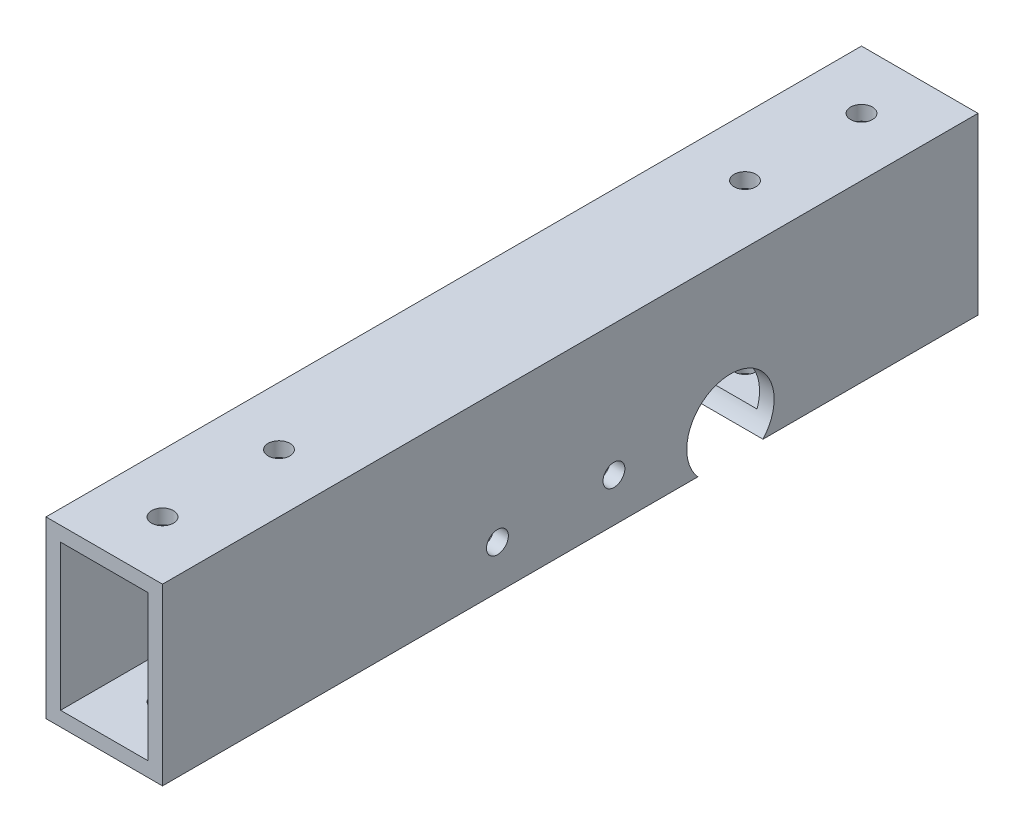
SolidWorks part; units mm, degrees
material "6063-T1"
ref_plane "Front Plane" through (0, 0, 0) normal (0, 0, 1) x (1, 0, 0)
ref_plane "Top Plane" through (0, 0, 0) normal (0, 1, 0) x (1, 0, 0)
ref_plane "Right Plane" through (0, 0, 0) normal (1, 0, 0) x (0, 0, -1)
sketch "Sketch1" plane through (0, 0, 0) normal (0, 0, 1) x (1, 0, 0)
  line L1 (-12.7, 19.05) -> (12.7, 19.05)
  line L2 (-12.7, 19.05) -> (-12.7, -19.05)
  line L3 (-12.7, -19.05) -> (12.7, -19.05)
  line L4 (12.7, 19.05) -> (12.7, -19.05)
  line L5 (-12.7, 19.05) -> (12.7, -19.05) construction
  line L6 (-12.7, -19.05) -> (12.7, 19.05) construction
  point P0 (0, 0)
  dimension "D1" = 25.4
  dimension "D2" = 38.1
extrude "Boss-Extrude1" add sketch "Sketch1" along normal blind 177.8
shell "Shell1" thickness 3.175
sketch "Sketch2" plane through (12.7, 0, 0) normal (1, 0, 0) x (0, 0, -1)
  line L0 (-177.8, -19.05) -> (0, -19.05) construction
  line L1 (0, -19.05) -> (0, 19.05) construction
  circle A0 centre (-53.975, -12.7) radius 9.525
  dimension "D1" = 19.05
  dimension "D2" = 6.35
  dimension "D3" = 53.975
extrude "Cut-Extrude1" cut sketch "Sketch2" against normal through all
sketch "Sketch3" plane through (0, 19.05, 0) normal (0, 1, 0) x (1, 0, 0)
  line L0 (12.7, -177.8) -> (-12.7, -177.8) construction
  circle A0 centre (0, -165.1) radius 2.3812
  circle A1 centre (0, -139.7) radius 2.3812
  dimension "D1" = 4.7625
  dimension "D3" = 4.7625
  dimension "D2" = 12.7
  dimension "D4" = 25.4
extrude "Cut-Extrude2" cut sketch "Sketch3" against normal through all
sketch "Sketch4" plane through (12.7, 0, 0) normal (1, 0, 0) x (0, 0, -1)
  line L0 (-177.8, -19.05) -> (-61.0745, -19.05) construction
  circle A0 centre (-79.375, -9.525) radius 2.3813
  circle A1 centre (-104.775, -9.525) radius 2.3813
  arc A2 (-46.8755, -19.05) -> (-61.0745, -19.05) centre (-53.975, -12.7) ccw construction
  dimension "D1" = 4.7625
  dimension "D2" = 4.7625
  dimension "D3" = 25.4
  dimension "D4" = 25.4
  dimension "D5" = 9.525
extrude "Cut-Extrude3" cut sketch "Sketch4" against normal through all
sketch "Sketch5" plane through (0, 19.05, 0) normal (0, 1, 0) x (1, 0, 0)
  line L0 (12.7, 0) -> (-12.7, 0) construction
  circle A0 centre (0, -12.7) radius 2.3813
  circle A1 centre (0, -38.1) radius 2.3812
  dimension "D1" = 4.7625
  dimension "D4" = 4.7625
  dimension "D2" = 12.7
  dimension "D3" = 25.4
extrude "Cut-Extrude4" cut sketch "Sketch5" against normal through all
